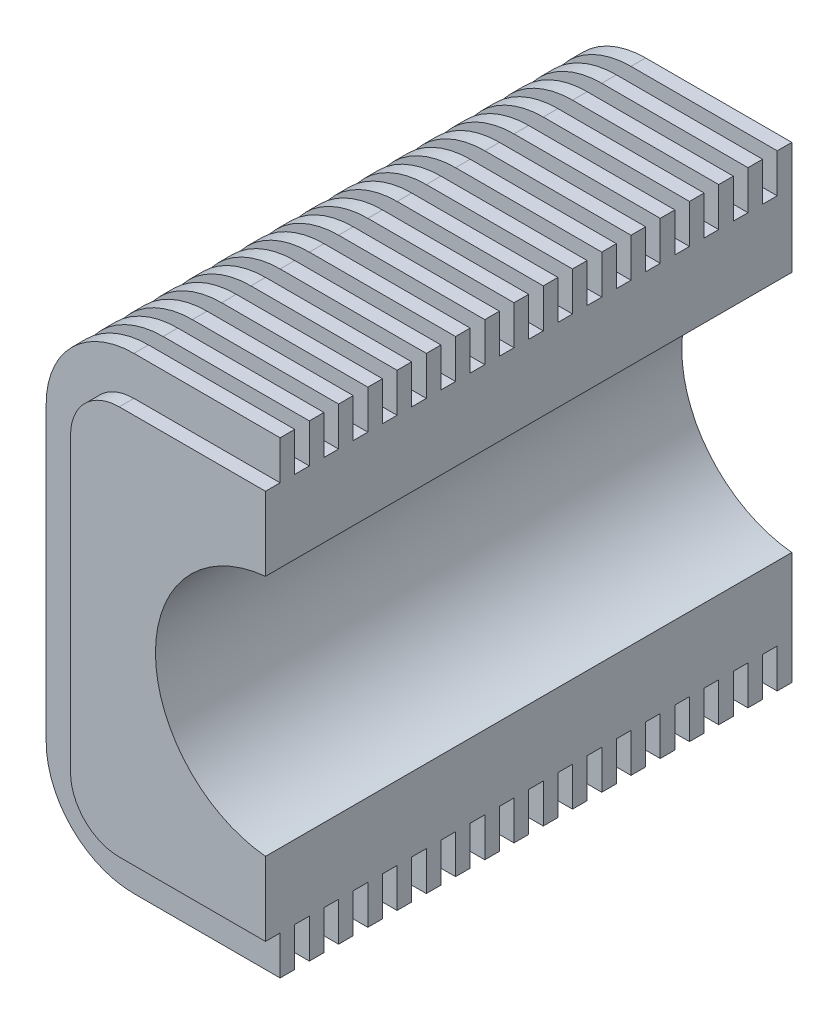
SolidWorks part; units mm, degrees
ref_plane "Płaszczyzna przednia" through (0, 0, 0) normal (0, 0, 1) x (1, 0, 0)
ref_plane "Płaszczyzna górna" through (0, 0, 0) normal (0, 1, 0) x (1, 0, 0)
ref_plane "Płaszczyzna prawa" through (0, 0, 0) normal (1, 0, 0) x (0, 0, -1)
sketch "Szkic1" plane through (0, 0, 0) normal (0, 0, 1) x (1, 0, 0)
  line L0 (0, 75) -> (-30, 75) construction
  line L1 (-40, 5) -> (-40, 65) construction
  line L2 (0, -5) -> (-30, -5) construction
  line L3 (0, 75) -> (-30, 75)
  line L4 (-40, 5) -> (-40, 65)
  line L5 (0, -5) -> (-30, -5)
  line L6 (0, -5) -> (0, 75)
  arc A0 (-30, 75) -> (-40, 65) centre (-30, 65) ccw construction
  arc A1 (-40, 5) -> (-30, -5) centre (-30, 5) ccw construction
  arc A2 (-30, 75) -> (-40, 65) centre (-30, 65) ccw
  arc A3 (-40, 5) -> (-30, -5) centre (-30, 5) ccw
extrude "Dodanie-wyciągnięcie1" add sketch "Szkic1" along normal blind 108
sketch "Szkic2" plane through (0, 0, 108) normal (0, 0, 1) x (1, 0, 0)
  circle A0 centre (2.4224, 35) radius 25 construction
  circle A1 centre (2.4224, 35) radius 25
extrude "Wytnij-wyciągnięcie1" cut sketch "Szkic2" against normal through all
sketch "Szkic3" plane through (0, 0, 0) normal (0, 0, -1) x (-1, 0, 0)
  line L0 (0, -13) -> (30, -13)
  line L1 (48, 5) -> (48, 65)
  line L2 (30, 83) -> (0, 83)
  line L3 (0, -13) -> (0, -5)
  line L4 (0, 83) -> (0, 75)
  line L5 (0, 75) -> (0, 59.8824)
  line L6 (0, 10.1176) -> (0, -5)
  line L7 (0, -5) -> (30, -5)
  line L8 (40, 5) -> (40, 65)
  line L9 (30, 75) -> (0, 75)
  line L10 (0, 75) -> (0, 59.8824)
  line L11 (0, 10.1176) -> (0, -5)
  line L12 (0, -5) -> (30, -5)
  line L13 (40, 5) -> (40, 65)
  line L14 (30, 75) -> (0, 75)
  arc A1 (30, -13) -> (48, 5) centre (30, 5) ccw
  arc A2 (48, 65) -> (30, 83) centre (30, 65) ccw
  arc A3 (0, 10.1176) -> (0, 59.8824) centre (-2.4224, 35) ccw
  arc A4 (30, -5) -> (40, 5) centre (30, 5) ccw
  arc A5 (40, 65) -> (30, 75) centre (30, 65) ccw
  arc A6 (0, 10.1176) -> (0, 59.8824) centre (-2.4224, 35) ccw
  arc A7 (30, -5) -> (40, 5) centre (30, 5) ccw
  arc A8 (40, 65) -> (30, 75) centre (30, 65) ccw
  line M13 (0, -5) -> (30, -5)
  arc M14 (30, -5) -> (40, 5) centre (30, 5) ccw
  line M15 (40, 5) -> (40, 65)
  arc M16 (40, 65) -> (30, 75) centre (30, 65) ccw
  line M17 (30, 75) -> (0, 75)
  dimension "D1" = 0
  dimension "D2" = 8
extrude "Dodanie-wyciągnięcie2" add sketch "Szkic3" against normal blind 3 contours L1 A2 L2 L4 L3 L0 A1 M17 M16 M15 M14 M13
pattern_linear "Szyk liniowy1" count 18 spacing 6 along (0, 0, 1) of "Dodanie-wyciągnięcie2"
